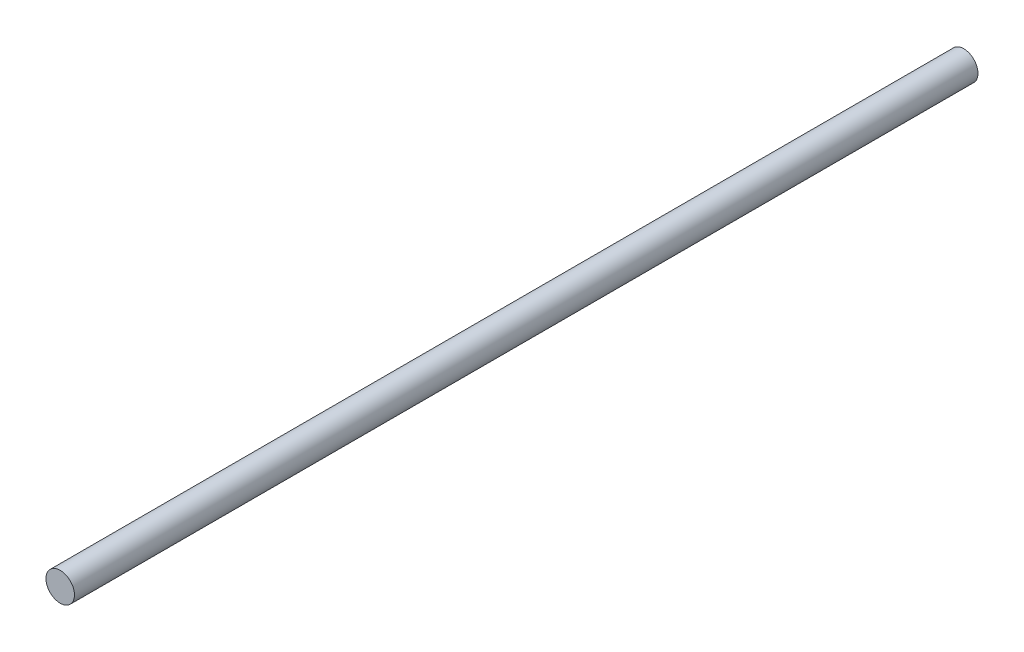
SolidWorks part; units mm, degrees
ref_plane "Front Plane" through (0, 0, 0) normal (0, 0, 1) x (1, 0, 0)
ref_plane "Top Plane" through (0, 0, 0) normal (0, 1, 0) x (1, 0, 0)
ref_plane "Right Plane" through (0, 0, 0) normal (1, 0, 0) x (0, 0, -1)
sketch "Sketch1" plane through (0, 0, 0) normal (0, 0, 1) x (1, 0, 0)
  circle A0 centre (0, 0) radius 2.5
  dimension "D1" = 5
extrude "Boss-Extrude1" add sketch "Sketch1" along normal blind 158.5
